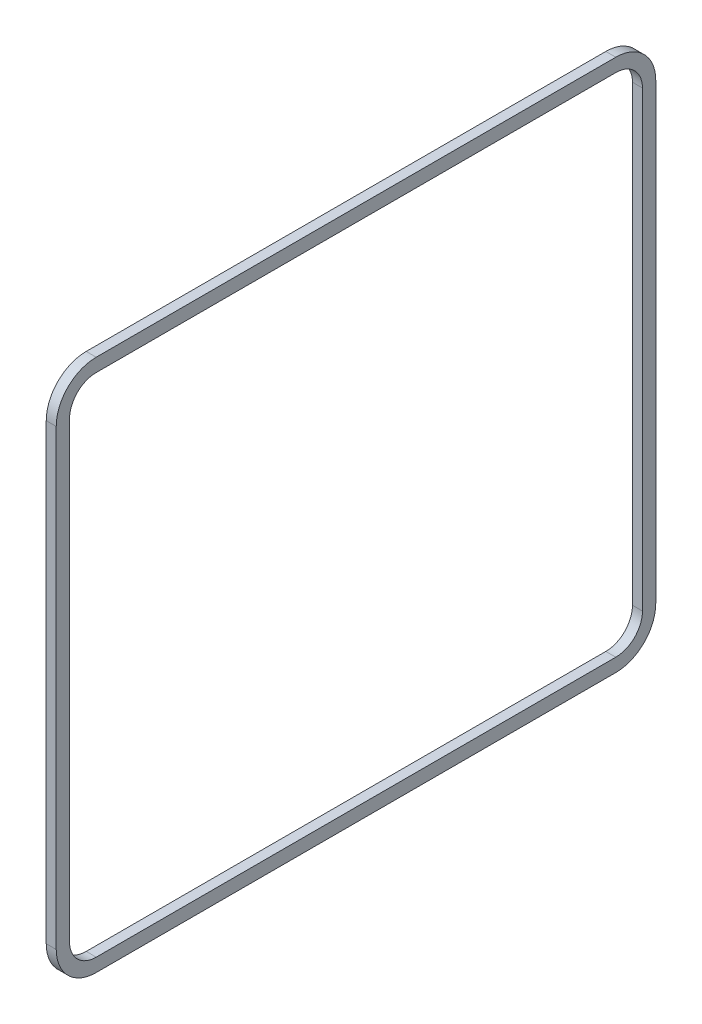
SolidWorks part; units mm, degrees
material "Copper"
ref_plane "Front Plane" through (0, 0, 0) normal (0, 0, 1) x (1, 0, 0)
ref_plane "Top Plane" through (0, 0, 0) normal (0, 1, 0) x (1, 0, 0)
ref_plane "Right Plane" through (0, 0, 0) normal (1, 0, 0) x (0, 0, -1)
sketch "Sketch1" plane through (0, 0, 0) normal (1, 0, 0) x (0, 0, -1)
  line L0 (39, 38) -> (-39, 38)
  line L1 (39, -40) -> (-39, -40)
  line L2 (45, -34) -> (45, 34)
  line L3 (39, 40) -> (-39, 40)
  line L4 (-45, -34) -> (-45, 34)
  line L5 (45, -40) -> (-45, 40) construction
  line L6 (45, 40) -> (-45, -40) construction
  line L7 (-43, -34) -> (-43, 34)
  line L8 (39, -38) -> (-39, -38)
  line L9 (43, -34) -> (43, 34)
  arc A0 (-45, -34) -> (-39, -40) centre (-39, -34) ccw
  arc A1 (39, -40) -> (45, -34) centre (39, -34) ccw
  arc A2 (45, 34) -> (39, 40) centre (39, 34) ccw
  arc A3 (-45, 34) -> (-39, 40) centre (-39, 34) cw
  arc A4 (-43, 34) -> (-39, 38) centre (-39, 34) cw
  arc A5 (-43, -34) -> (-39, -38) centre (-39, -34) ccw
  arc A6 (39, -38) -> (43, -34) centre (39, -34) ccw
  arc A7 (43, 34) -> (39, 38) centre (39, 34) ccw
  point P0 (0, 0)
  dimension "D3" = 6
  dimension "D1" = 90
  dimension "D2" = 80
  dimension "D4" = 2
extrude "Boss-Extrude1" add sketch "Sketch1" along normal blind 1.5
